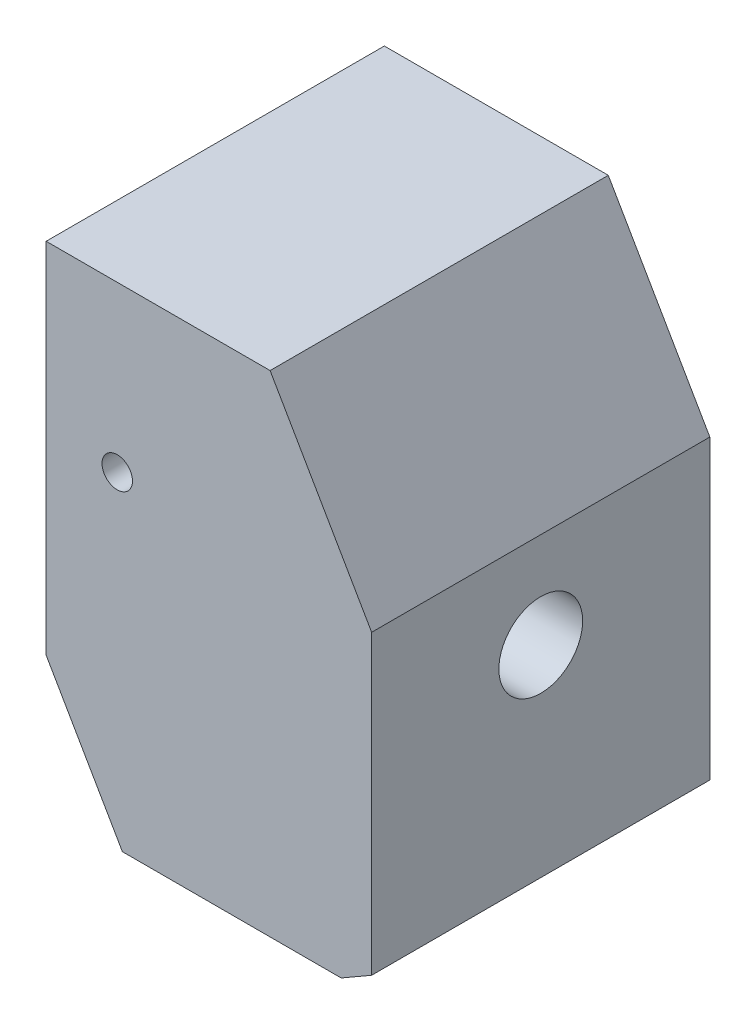
SolidWorks part; units mm, degrees
ref_plane "Front Plane" through (0, 0, 0) normal (0, 0, 1) x (1, 0, 0)
ref_plane "Top Plane" through (0, 0, 0) normal (0, 1, 0) x (1, 0, 0)
ref_plane "Right Plane" through (0, 0, 0) normal (1, 0, 0) x (0, 0, -1)
sketch "Sketch1" plane through (0, 0, 0) normal (1, 0, 0) x (0, 0, -1)
  line L1 (-16.65, 24.15) -> (16.65, 24.15)
  line L2 (-16.65, 24.15) -> (-16.65, -24.15)
  line L3 (-16.65, -24.15) -> (16.65, -24.15)
  line L4 (16.65, 24.15) -> (16.65, -24.15)
  line L5 (-16.65, 24.15) -> (16.65, -24.15) construction
  line L6 (-16.65, -24.15) -> (16.65, 24.15) construction
  point P0 (0, 0)
  dimension "D1" = 48.3
  dimension "D2" = 33.3
extrude "Boss-Extrude1" add sketch "Sketch1" along normal blind 9.55
sketch "Sketch2" plane through (0, 0, 0) normal (-1, 0, 0) x (0, 0, 1)
  line L0 (0, 24.15) -> (0, 19.15) construction
  line L3 (-16.65, 24.15) -> (16.65, 24.15) construction
  line L4 (0, 19.15) -> (0, -19.451) construction
  line L5 (0, -19.451) -> (0, -24.15) construction
  line L6 (16.65, -24.15) -> (-16.65, -24.15) construction
  line L7 (0, 19.15) -> (-5.65, 19.15)
  line L8 (-5.65, 19.15) -> (-5.65, 5.45)
  line L9 (-5.65, 5.45) -> (-11.65, -0.9874)
  line L10 (-11.65, -0.9874) -> (-11.65, -9.1)
  line L11 (-11.65, -9.1) -> (-10.5771, -10.1)
  line L12 (-10.5771, -10.1) -> (10.5771, -10.1)
  line L13 (11.65, -9.1) -> (10.5771, -10.1)
  line L14 (11.65, -0.9874) -> (11.65, -9.1)
  line L15 (5.65, 5.45) -> (11.65, -0.9874)
  line L16 (5.65, 5.45) -> (5.65, 11.45)
  line L17 (5.65, 11.45) -> (4.5, 12.6)
  line L18 (4.5, 12.6) -> (4.5, 19.15)
  line L19 (4.5, 19.15) -> (0, 19.15)
  point P16 (0, -10.1)
  dimension "D1" = 5
  dimension "D2" = 4.699
  dimension "D3" = 11.65
  dimension "D4" = 15.55
  dimension "D5" = 5.65
  dimension "D6" = 13.7
  dimension "D7" = 8.8
  dimension "D8" = 1
  dimension "D9" = 6
  dimension "D10" = 7.15
  dimension "D11" = 4.5
extrude "Cut-Extrude1" cut sketch "Sketch2" against normal blind 5
sketch "Sketch3" plane through (5, 0, 0) normal (-1, 0, 0) x (0, 0, 1)
  line L0 (-5.65, 19.15) -> (4.5, 19.15)
  line L1 (4.5, 19.15) -> (4.5, 12.6)
  line L2 (4.5, 12.6) -> (5.65, 11.45)
  line L3 (5.65, 11.45) -> (5.65, 5.45)
  line L4 (5.65, 5.45) -> (-5.65, 5.45)
  line L5 (-5.65, 5.45) -> (-5.65, 19.15)
extrude "Cut-Extrude2" cut sketch "Sketch3" against normal blind 4.5
sketch "Sketch5" plane through (9.55, 0, 0) normal (1, 0, 0) x (0, 0, -1)
  line L1 (-16.65, 24.15) -> (16.65, 24.15)
  line L2 (-16.65, 24.15) -> (-16.65, -24.15)
  line L3 (-16.65, -24.15) -> (16.65, -24.15)
  line L4 (16.65, 24.15) -> (16.65, -24.15)
  line L5 (-16.65, 24.15) -> (16.65, -24.15) construction
  line L6 (-16.65, -24.15) -> (16.65, 24.15) construction
  point P0 (0, 0)
extrude "Boss-Extrude3" add sketch "Sketch5" along normal blind 22.5
sketch "Sketch6" plane through (5, 0, 0) normal (-1, 0, 0) x (0, 0, 1)
  line L0 (0, 5.45) -> (0, -2.575) construction
  line L1 (-5.65, 5.45) -> (5.65, 5.45) construction
  line L2 (0, 1.45) -> (5.4752, 1.45) construction
  circle A0 centre (0, -2.575) radius 4.025
  dimension "D2" = 8.05
  dimension "D1" = 4
extrude "Cut-Extrude3" cut sketch "Sketch6" against normal blind 12
sketch "Sketch7" plane through (17, 0, 0) normal (-1, 0, 0) x (0, 0, 1)
  circle A0 centre (0, -2.575) radius 4.125
  dimension "D1" = 8.25
extrude "Cut-Extrude4" cut sketch "Sketch7" against normal up to surface (15.05 mm away) up to face at (32.05, 0, 0)
sketch "Sketch27" plane through (0, 0, 5.65) normal (0, 0, -1) x (-1, 0, 0)
  line L0 (-9.5, 5.45) -> (-9.5, 11.45) construction
  line L1 (-9.5, 5.45) -> (-5, 5.45) construction
  circle A0 centre (-7, 7.95) radius 1.5
  dimension "D1" = 3
  dimension "D2" = 2.5
  dimension "D3" = 2.5
extrude "Cut-Extrude6" cut sketch "Sketch27" against normal through all both and the other way through all
ref_plane "Plane1" through (18.4698, -31.9906, 0) normal (0.5, -0.866, 0) x (0, 0, -1)
sketch "Sketch28" plane through (0, 0, 0) normal (0, 0, 1) x (1, 0, 0)
  line L0 (32.05, -2.575) -> (17, -2.575) construction
  line L1 (32.05, -6.7) -> (32.05, 1.55) construction
  line L2 (17, -6.6) -> (17, 1.45) construction
  line L3 (17, -2.575) -> (17, -6.6) construction
  line L4 (17, -6.7) -> (17, 1.55) construction
  line L5 (17, -6.6) -> (13, -6.6) construction
  line L6 (13, -6.6) -> (25.3619, -28.0114)
  line L7 (3.2039, -40.8043) -> (33.7356, -23.1768) construction
  line L8 (13, -6.6) -> (10.1841, -1.7228)
  dimension "D1" = 4.025
  dimension "D2" = 4
  dimension "D3" = 60
  dimension "D4" = 180
sketch "Sketch29" plane through (0, 0, 0) normal (0, 0, 1) x (1, 0, 0)
  line L0 (32.05, -2.575) -> (17, -2.575) construction
  line L1 (32.05, -6.7) -> (32.05, 1.55) construction
  line L2 (19, -16.9923) -> (25.3619, -28.0114)
  line L3 (17, -2.575) -> (17, -6.6) construction
  line L4 (3.2039, -40.8043) -> (33.7356, -23.1768) construction
  line L5 (17, -6.6) -> (13, -6.6) construction
  line L6 (13, -6.6) -> (19, -16.9923) construction
  line L8 (13, -6.6) -> (25.3619, -28.0114) construction
  dimension "D1" = 4.025
  dimension "D2" = 4
  dimension "D3" = 12
  dimension "D4" = 60
sketch "Sketch30" plane through (18.4698, -31.9906, 0) normal (0.5, -0.866, 0) x (0, 0, -1)
  circle A0 centre (0, 7.9583) radius 4
  dimension "D1" = 8
sweep "Cut-Sweep1" cut profiles "Sketch30" path "Sketch28"
sketch "Sketch31" plane through (18.4698, -31.9906, 0) normal (0.5, -0.866, 0) x (0, 0, -1)
  circle A0 centre (0, 7.9583) radius 5
  dimension "D1" = 10
sweep "Cut-Sweep2" cut profiles "Sketch31" path "Sketch29"
chamfer "Chamfer1" distance 13 angle 30 1 edges at (0, -24.15, 0)
chamfer "Chamfer2" distance 10 angle 60 1 edges at (32.05, 24.15, 0)
chamfer "Chamfer3" distance 3 angle 30 1 edges at (32.05, -24.15, 0)
